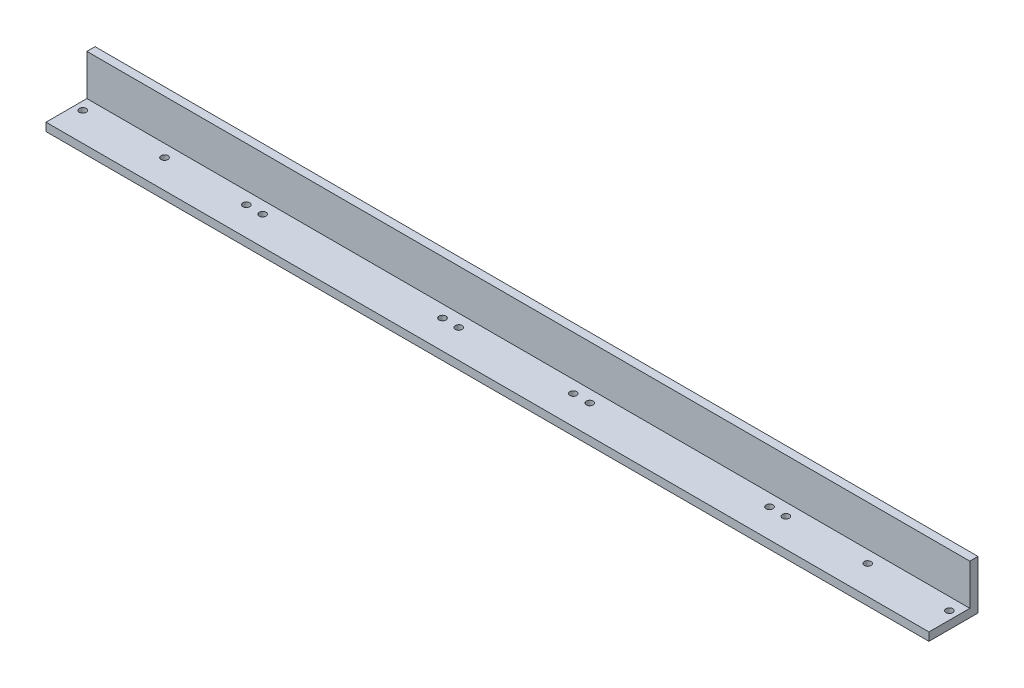
SolidWorks part; units mm, degrees
material "6063-O"
ref_plane "Front Plane" through (0, 0, 0) normal (0, 0, 1) x (1, 0, 0)
ref_plane "Top Plane" through (0, 0, 0) normal (0, 1, 0) x (1, 0, 0)
ref_plane "Right Plane" through (0, 0, 0) normal (1, 0, 0) x (0, 0, -1)
sketch "Sketch1" plane through (0, 0, 0) normal (1, 0, 0) x (0, 0, -1)
  line L0 (-38.1, 0) -> (0, 0)
  line L1 (55, 0) -> (-55, 0) construction
  line L2 (0, 0) -> (0, 38.1)
  line L3 (0, 55) -> (0, -55) construction
  dimension "D1" = 38.1
  dimension "D2" = 38.1
extrude "Extrude-Thin1" add sketch "Sketch1" along normal mid plane 685.8 thin thin type one direction reverse wall 6.35
sketch "Sketch2" plane through (0, 6.35, 0) normal (0, 1, 0) x (1, 0, 0)
  circle A0 centre (-336.55, -15.875) radius 2.667 construction
  circle A1 centre (-336.55, -15.875) radius 2.667
  circle A2 centre (-273.05, -15.875) radius 2.667 construction
  circle A3 centre (-273.05, -15.875) radius 2.667
  circle A4 centre (-209.55, -15.875) radius 2.667 construction
  circle A5 centre (-209.55, -15.875) radius 2.667
  circle A6 centre (-196.85, -15.875) radius 2.667 construction
  circle A7 centre (-196.85, -15.875) radius 2.667
  circle A8 centre (-57.15, -15.875) radius 2.667 construction
  circle A9 centre (-57.15, -15.875) radius 2.667
  circle A10 centre (-44.45, -15.875) radius 2.667 construction
  circle A11 centre (-44.45, -15.875) radius 2.667
  circle A12 centre (44.45, -15.875) radius 2.667 construction
  circle A13 centre (44.45, -15.875) radius 2.667
  circle A14 centre (57.15, -15.875) radius 2.667 construction
  circle A15 centre (57.15, -15.875) radius 2.667
  circle A16 centre (196.85, -15.875) radius 2.667 construction
  circle A17 centre (196.85, -15.875) radius 2.667
  circle A18 centre (209.55, -15.875) radius 2.667 construction
  circle A19 centre (209.55, -15.875) radius 2.667
  circle A22 centre (336.55, -15.875) radius 2.667 construction
  circle A23 centre (336.55, -15.875) radius 2.667
  circle A24 centre (273.05, -15.875) radius 2.667 construction
  circle A25 centre (273.05, -15.875) radius 2.667
extrude "Cut-Extrude4" cut sketch "Sketch2" against normal up to next
